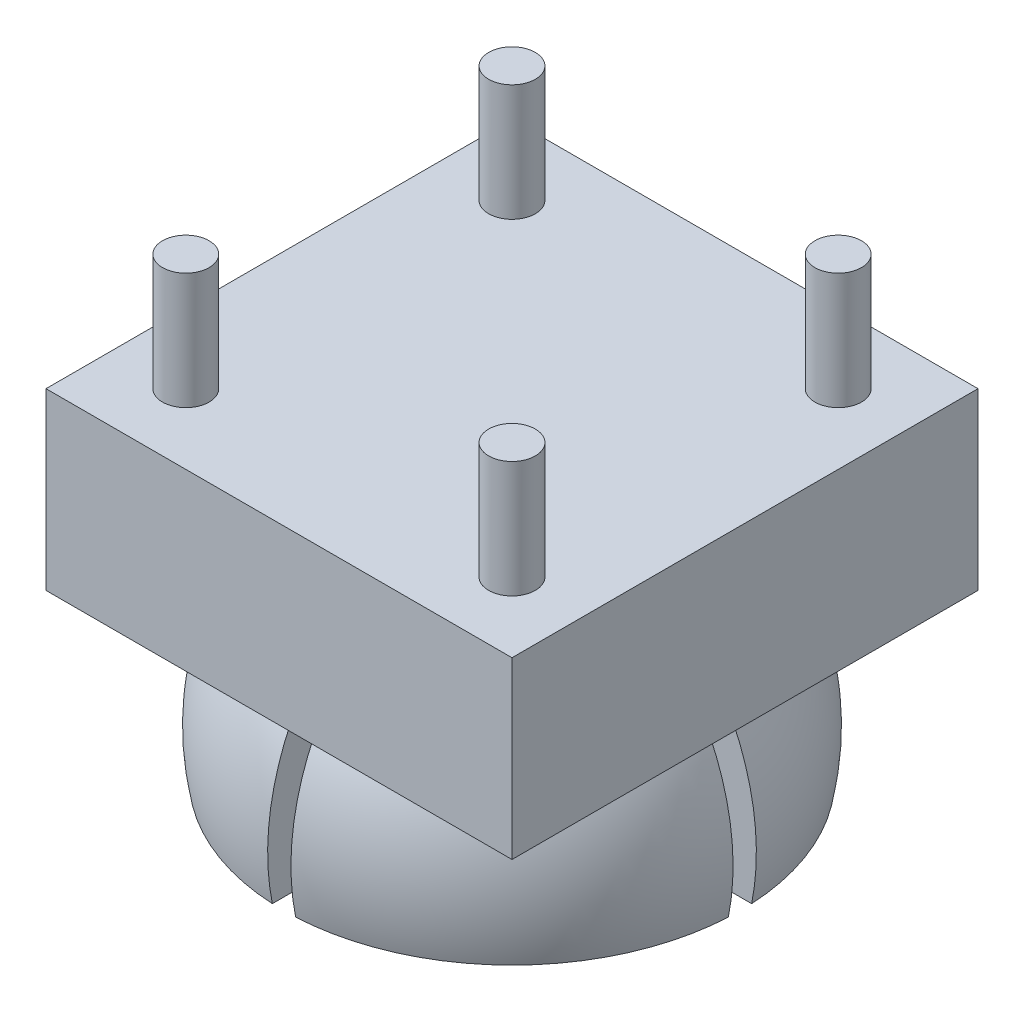
SolidWorks part; units mm, degrees
ref_plane "Front Plane" through (0, 0, 0) normal (0, 0, 1) x (1, 0, 0)
ref_plane "Top Plane" through (0, 0, 0) normal (0, 1, 0) x (1, 0, 0)
ref_plane "Right Plane" through (0, 0, 0) normal (1, 0, 0) x (0, 0, -1)
sketch "Sketch1" plane through (0, 0, 0) normal (0, 1, 0) x (1, 0, 0)
  line L1 (-5.1923, -3.1571) -> (14.8077, -3.1571)
  line L2 (-5.1923, -3.1571) -> (-5.1923, 16.8429)
  line L3 (-5.1923, 16.8429) -> (14.8077, 16.8429)
  line L4 (14.8077, -3.1571) -> (14.8077, 16.8429)
  dimension "D1" = 20
  dimension "D2" = 20
extrude "Boss-Extrude1" add sketch "Sketch1" along normal blind 7.5
ref_plane "Plane1" through (0, 0, -6.8429) normal (0, 0, 1) x (1, 0, 0)
sketch "Sketch3" plane through (0, 0, -6.8429) normal (0, 0, 1) x (1, 0, 0)
  line L0 (-5.1923, 7.5) -> (14.8077, 7.5) construction
  line L1 (4.8077, 5) -> (4.8077, -15)
  line L2 (4.8077, 3) -> (4.8077, 5)
  line L3 (4.8077, -13) -> (4.8077, -15) construction
  line L4 (4.8077, -15) -> (4.8077, -13)
  line L5 (4.8077, -13) -> (-5.1968, -15.5077)
  line L6 (4.8077, 3) -> (4.8077, 5)
  line L7 (14.8077, 7.5) -> (14.8077, 0) construction
  arc A0 (4.8077, -15) -> (4.8077, 5) centre (4.8077, -5) ccw
  arc A1 (4.8077, -13) -> (4.8077, 3) centre (4.8077, -5) ccw
  dimension "D1" = 12.5
  dimension "D2" = 20
  dimension "D3" = 16
  dimension "D4" = 10
revolve "Cut-Revolve3" cut sketch "Sketch3" angle 360 about L1
sketch "Sketch5" plane through (0, 0, -6.8429) normal (0, 0, 1) x (1, 0, 0)
  line L1 (4.8077, 5) -> (4.8077, -15) construction
  line L2 (4.8077, 3) -> (4.8077, 5)
  line L3 (4.8077, -13) -> (4.8077, -15) construction
  line L4 (4.8077, -15) -> (4.8077, -13)
  line L5 (4.8077, -13) -> (4.8032, -13.0077)
  line L6 (4.8077, 3) -> (4.8077, 5)
  line L7 (-5.1923, 7.5) -> (14.8077, 7.5) construction
  line L8 (-5.1923, 7.5) -> (-5.1923, 0) construction
  arc A0 (4.8077, -15) -> (4.8077, 5) centre (4.8077, -5) ccw
  arc A1 (4.8077, -13) -> (4.8077, 3) centre (4.8077, -5) ccw
  dimension "D1" = 10
  dimension "D2" = 20
  dimension "D3" = 16
  dimension "D4" = 12.5
revolve "Revolve7" add sketch "Sketch5" angle 360 about L1
ref_plane "Plane2" through (0, -15, 0) normal (0, -1, 0) x (-1, 0, 0)
sketch "Sketch6" plane through (0, -15, 0) normal (0, -1, 0) x (-1, 0, 0)
  line L0 (-12.8077, 6.8429) -> (-4.8077, 6.8429) construction
  line L1 (5.1923, 16.8429) -> (-14.8077, 16.8429)
  line L2 (5.1923, 16.8429) -> (5.1923, -3.1571)
  line L3 (5.1923, -3.1571) -> (-14.8077, -3.1571)
  line L4 (-14.8077, 16.8429) -> (-14.8077, -3.1571)
  dimension "D1" = 20
  dimension "D2" = 20
  dimension "D3" = 10
  dimension "D4" = 10
extrude "Cut-Extrude1" cut sketch "Sketch6" against normal blind 8
sketch "Sketch8" plane through (0, 7.5, 0) normal (0, 1, 0) x (1, 0, 0)
  line L0 (-5.1923, 16.8429) -> (-5.1923, -3.1571) construction
  line L1 (-5.1923, -3.1571) -> (14.8077, -3.1571) construction
  line L2 (14.8077, 16.8429) -> (-5.1923, 16.8429) construction
  line L3 (14.8077, -3.1571) -> (14.8077, 16.8429) construction
  line L4 (14.8077, -3.1571) -> (14.8077, 16.8429) construction
  circle A0 centre (-2.1923, -0.1571) radius 1
  circle A1 centre (-2.1923, 13.8429) radius 1
  circle A2 centre (11.8077, -0.1571) radius 1
  circle A3 centre (11.8077, 13.8429) radius 1
  dimension "D1" = 2
  dimension "D2" = 3
  dimension "D3" = 3
  dimension "D4" = 2
  dimension "D5" = 3
  dimension "D6" = 3
  dimension "D7" = 2
  dimension "D8" = 3
  dimension "D9" = 3
  dimension "D10" = 2
  dimension "D11" = 3
  dimension "D12" = 3
extrude "Boss-Extrude3" add sketch "Sketch8" along normal blind 5
sketch "Sketch9" plane through (0, 0, -6.8429) normal (0, 0, 1) x (1, 0, 0)
  line L0 (-5.1923, 0) -> (14.8077, 0) construction
  line L1 (-5.1923, 0) -> (14.8077, 0)
  line L2 (-5.1923, 0) -> (-5.1923, -7)
  line L3 (-5.1923, -7) -> (14.8077, -7)
  line L4 (14.8077, 0) -> (14.8077, -7)
  line L5 (-5.1923, 7.5) -> (-5.1923, 0) construction
  line L6 (14.8077, 7.5) -> (14.8077, 0) construction
  line L7 (-4.9903, -7) -> (14.6057, -7) construction
  dimension "D1" = 0
  dimension "D2" = 0
  dimension "D3" = 0
  dimension "D4" = 0
extrude "Cut-Extrude2" cut sketch "Sketch9" against normal blind 0.5 and the other way blind 0.5
ref_plane "Plane3" through (4.8077, 0, 0) normal (-1, 0, 0) x (0, 0, 1)
sketch "Sketch10" plane through (4.8077, 0, 0) normal (-1, 0, 0) x (0, 0, 1)
  line L0 (-16.8429, 7.5) -> (-16.8429, 0) construction
  line L1 (-16.8429, -7) -> (3.1571, -7)
  line L2 (-16.8429, -7) -> (-16.8429, 0)
  line L3 (-16.8429, 0) -> (3.1571, 0)
  line L4 (3.1571, -7) -> (3.1571, 0)
  line L5 (3.1571, 7.5) -> (3.1571, 0) construction
  line L6 (-16.8429, 0) -> (3.1571, 0) construction
  line L7 (-6.3429, -7) -> (2.955, -7) construction
  dimension "D1" = 0
  dimension "D2" = 0
  dimension "D3" = 0
  dimension "D4" = 0
extrude "Cut-Extrude3" cut sketch "Sketch10" against normal blind 0.5 and the other way blind 0.5
